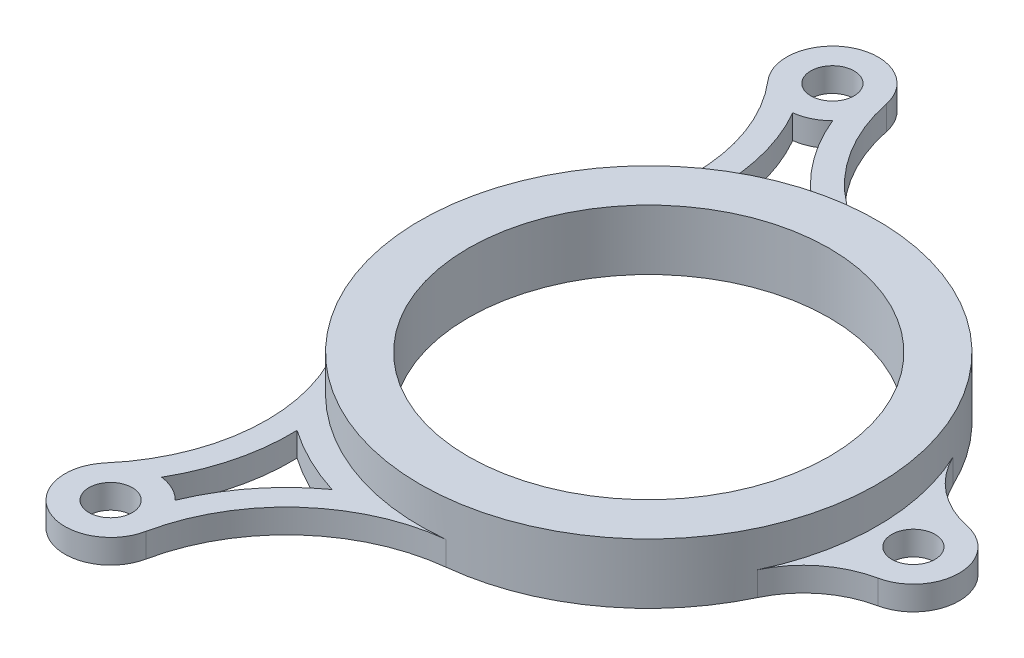
SolidWorks part; units mm, degrees
ref_plane "Front Plane" through (0, 0, 0) normal (0, 0, 1) x (1, 0, 0)
ref_plane "Top Plane" through (0, 0, 0) normal (0, 1, 0) x (1, 0, 0)
ref_plane "Right Plane" through (0, 0, 0) normal (1, 0, 0) x (0, 0, -1)
sketch "Sketch1" plane through (0, 0, 0) normal (0, 1, 0) x (1, 0, 0)
  circle A0 centre (0, 0) radius 19.05
  circle A1 centre (0, 0) radius 24.13
  dimension "D1" = 5.08
  dimension "D2" = 38.1
extrude "Boss-Extrude1" add sketch "Sketch1" along normal blind 6.35
sketch "Sketch2" plane through (0, 0, 0) normal (0, -1, 0) x (1, 0, 0)
  line L0 (21.8096, 10.3246) -> (21.8096, -10.3246)
  circle A0 centre (27.94, 0) radius 2.286
  circle A2 centre (0, 0) radius 24.13 construction
  circle A3 centre (0, 0) radius 24.13 construction
  arc A4 (21.8096, 10.3246) -> (28.923, 4.7248) centre (30.9926, 14.6718) ccw
  arc A5 (28.923, -4.7248) -> (21.8096, -10.3246) centre (30.9926, -14.6718) ccw
  arc A6 (28.923, -4.7248) -> (28.923, 4.7248) centre (27.94, 0) ccw
  point P2 (29.204, 0)
  point P3 (0, 0)
  point P7 (0, 0)
  dimension "D1" = 4.572
  dimension "D3" = 10.16
  dimension "D4" = 10.16
  dimension "D2" = 2.54
  dimension "D5" = 27.94
extrude "Boss-Extrude2" add sketch "Sketch2" against normal blind 2.54
sketch "Sketch3" plane through (0, 0, 0) normal (0, -1, 0) x (1, 0, 0)
  circle A0 centre (-18.7096, 38.1) radius 2.286
  arc A1 (-22.3714, 34.9564) -> (-13.9833, 39.0755) centre (-18.7096, 38.1) ccw
  arc A2 (-20.579, 12.6001) -> (-22.3714, 34.9564) centre (-36.8255, 22.5476) ccw
  arc A3 (21.8096, 10.3246) -> (21.8096, -10.3246) centre (0, 0) ccw construction
  arc A4 (-13.9833, 39.0755) -> (2.6116, 23.9883) centre (4.6735, 42.9263) ccw
  arc A5 (-13.9833, 39.0755) -> (-22.3714, 34.9564) centre (-18.7096, 38.1) ccw
  circle A6 centre (-18.7096, 38.1) radius 4.826 construction
  arc A7 (2.6116, 23.9883) -> (-20.579, 12.6001) centre (0, 0) ccw
  arc A8 (-15.2869, 34.6977) -> (-7.9946, 25.4436) centre (4.6735, 42.9263) ccw
  arc A9 (-7.9946, 25.4436) -> (-15.2458, 21.8828) centre (0, 0) ccw
  arc A10 (-15.2458, 21.8828) -> (-18.1101, 33.3114) centre (-36.8255, 22.5476) ccw
  arc A11 (-16.4708, 38.5621) -> (-7.9946, 25.4436) centre (4.6735, 42.9263) ccw construction
  arc A12 (-15.2458, 21.8828) -> (-20.4441, 36.6109) centre (-36.8255, 22.5476) ccw construction
  point P3 (-20.9876, 33.8455)
  point P7 (-37.3218, 22.5085)
  arc M4 (21.8096, 10.3246) -> (21.8096, -10.3246) centre (0, 0) ccw
  dimension "D2" = 4.572
  dimension "D4" = 38.1
  dimension "D5" = 19.05
  dimension "D6" = 19.05
  dimension "D3" = 18.7096
  dimension "D1" = 2.54
  dimension "D7" = 2.54
extrude "Boss-Extrude3" add sketch "Sketch3" against normal blind 2.54 contours A9 A10 A1 A2 A4 A8 M4 | A1 A5 A0
mirror "Mirror1" about plane through (0, 0, 0) normal (0, 0, 1) of "Boss-Extrude3"
